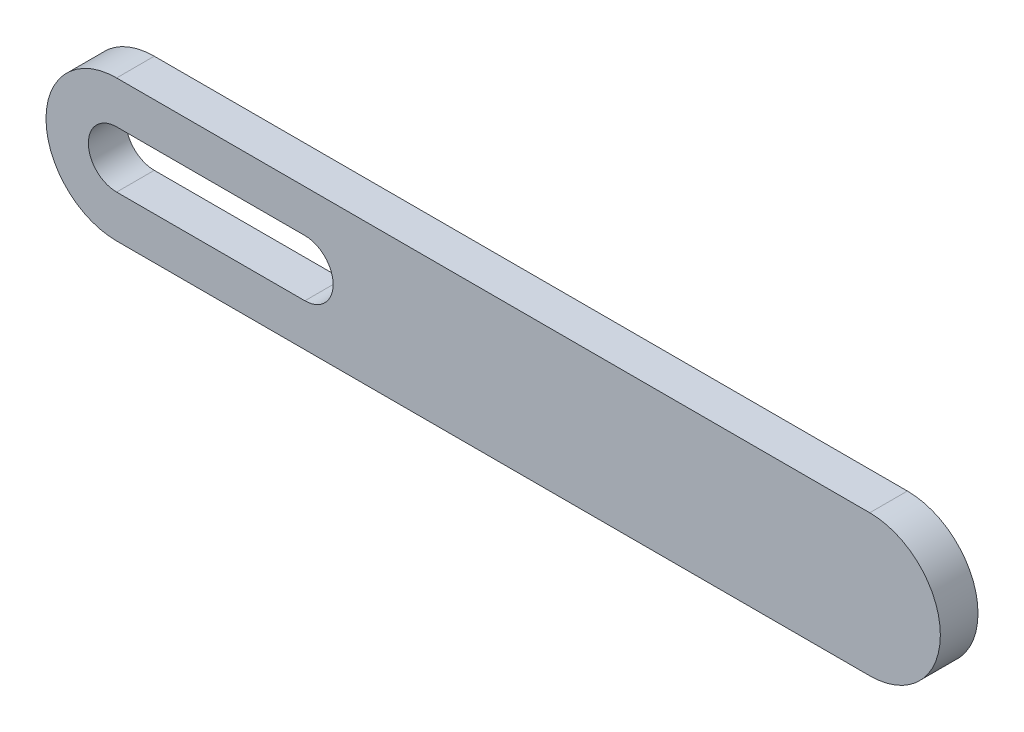
SolidWorks part; units mm, degrees
ref_plane "Front" through (0, 0, 0) normal (0, 0, 1) x (1, 0, 0)
ref_plane "Top" through (0, 0, 0) normal (0, 1, 0) x (1, 0, 0)
ref_plane "Right" through (0, 0, 0) normal (1, 0, 0) x (0, 0, -1)
sketch "Sketch1" plane through (0, 0, 0) normal (0, 0, 1) x (1, 0, 0)
  line L0 (-50, 15) -> (50, -15) construction
  line L1 (-50, 37.5) -> (350, 37.5)
  line L2 (-50, 0) -> (350, 0) construction
  line L3 (-50, -37.5) -> (350, -37.5)
  line L4 (50, 0) -> (-50, 0) construction
  line L5 (-50, 15) -> (50, 15)
  line L7 (-50, -15) -> (50, -15)
  arc A0 (-50, 37.5) -> (-50, -37.5) centre (-50, 0) ccw
  arc A1 (350, 37.5) -> (350, -37.5) centre (350, 0) cw
  arc A2 (-50, 15) -> (-50, -15) centre (-50, 0) ccw
  arc A3 (50, 15) -> (50, -15) centre (50, 0) cw
  dimension "D1" = 75
  dimension "D2" = 30
  dimension "D3" = 100
  dimension "D4" = 400
extrude "Extrude1" add sketch "Sketch1" along normal blind 20
